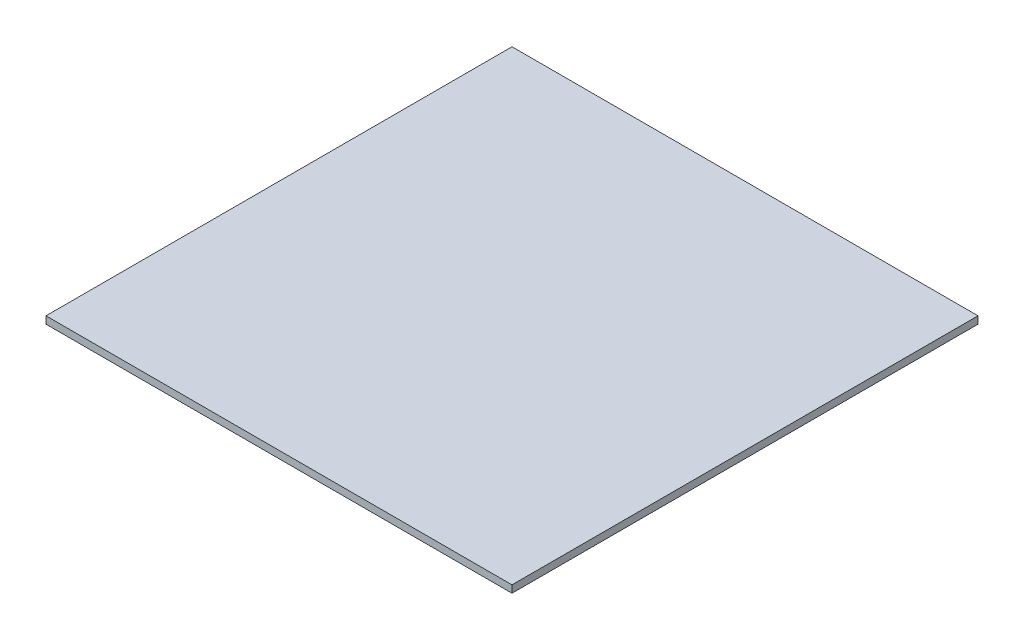
SolidWorks part; units mm, degrees
ref_plane "Front Plane" through (0, 0, 0) normal (0, 0, 1) x (1, 0, 0)
ref_plane "Top Plane" through (0, 0, 0) normal (0, 1, 0) x (1, 0, 0)
ref_plane "Right Plane" through (0, 0, 0) normal (1, 0, 0) x (0, 0, -1)
sketch "Sketch2" plane through (0, 0, 0) normal (0, 1, 0) x (1, 0, 0)
  line L1 (-101.6, -101.6) -> (101.6, -101.6)
  line L2 (-101.6, -101.6) -> (-101.6, 101.6)
  line L3 (-101.6, 101.6) -> (101.6, 101.6)
  line L4 (101.6, -101.6) -> (101.6, 101.6)
  line L5 (-101.6, -101.6) -> (101.6, 101.6) construction
  line L6 (-101.6, 101.6) -> (101.6, -101.6) construction
  point P0 (0, 0)
  dimension "D1" = 203.2
extrude "Boss-Extrude1" add sketch "Sketch2" along normal blind 3.175
